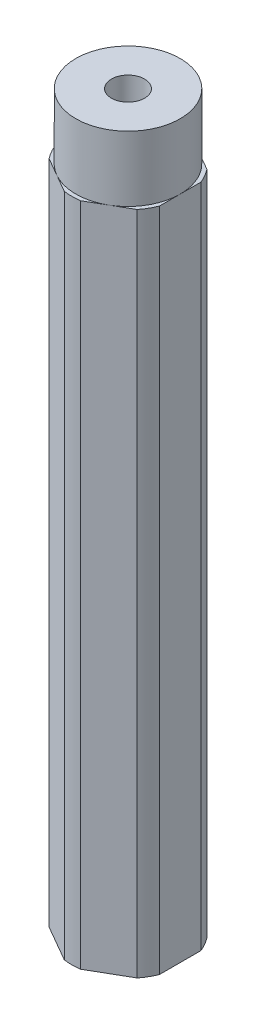
SolidWorks part; units mm, degrees
material "7075-T6 (SN)"
ref_plane "Front Plane" through (0, 0, 0) normal (0, 0, 1) x (1, 0, 0)
ref_plane "Top Plane" through (0, 0, 0) normal (0, 1, 0) x (1, 0, 0)
ref_plane "Right Plane" through (0, 0, 0) normal (1, 0, 0) x (0, 0, -1)
sketch "Sketch1" plane through (0, 0, 0) normal (0, 1, 0) x (1, 0, 0)
  line L1 (0, 7.3323) -> (-6.35, 3.6662)
  line L2 (-6.35, 3.6662) -> (-6.35, -3.6662)
  line L3 (-6.35, -3.6662) -> (0, -7.3323)
  line L4 (0, -7.3323) -> (6.35, -3.6662)
  line L5 (6.35, -3.6662) -> (6.35, 3.6662)
  line L6 (6.35, 3.6662) -> (0, 7.3323)
  circle A0 centre (0, 0) radius 6.35 construction
  circle A1 centre (0, 0) radius 6.8326
  dimension "D1" = 12.7
  dimension "D2" = 13.6652
extrude "Boss-Extrude1" add sketch "Sketch1" along normal mid plane 80.9625 contours L4 A1 L5 L6 L1 L2 L3
sketch "Sketch3" plane through (0, 40.4812, 0) normal (0, 1, 0) x (1, 0, 0)
  line L0 (5.3594, 4.2381) -> (0.9906, 6.7604) construction
  circle A0 centre (0, 0) radius 6.35
extrude "Boss-Extrude2" add sketch "Sketch3" along normal blind 7.9375
hole_wizard "#10-32 Tapped Hole1" positions "Sketch4" profile "Sketch5" tap size "#10-32" standard "ANSI Inch"
sketch "Sketch4" plane through (0, -40.4812, 0) normal (0, -1, 0) x (-1, 0, 0)
  point P0 (0, 0)
sketch "Sketch5" plane through (0, -40.4812, 0) normal (1, 0, 0) x (0, 0, -1)
  line L0 (0, 0) -> (0, 13.2428)
  line L1 (0, 13.2428) -> (2.0193, 12.0294)
  line L2 (2.0193, 12.0294) -> (2.0193, 0)
  line L5 (2.0193, 0) -> (0, 0)
  line L10 (0, 13.2428) -> (-2.0193, 12.0294) construction
  line L11 (0, -6.35) -> (0, 107.95) construction
  dimension "Tap Drill Dia." = 4.0386
  dimension "Tap Drill Depth" = 12.0294
  dimension "Drill Angle" = 118
cosmetic thread "Hole Thread1" parameters "D1"=9.652, "D2"=5.0386
sketch "Sketch2" plane through (0, -40.4812, 0) normal (0, 1, 0) x (1, 0, 0)
  circle A0 centre (0, 0) radius 2.0193
  dimension "D1" = 4.0386
extrude "Cut-Extrude1" cut sketch "Sketch2" along normal through all
